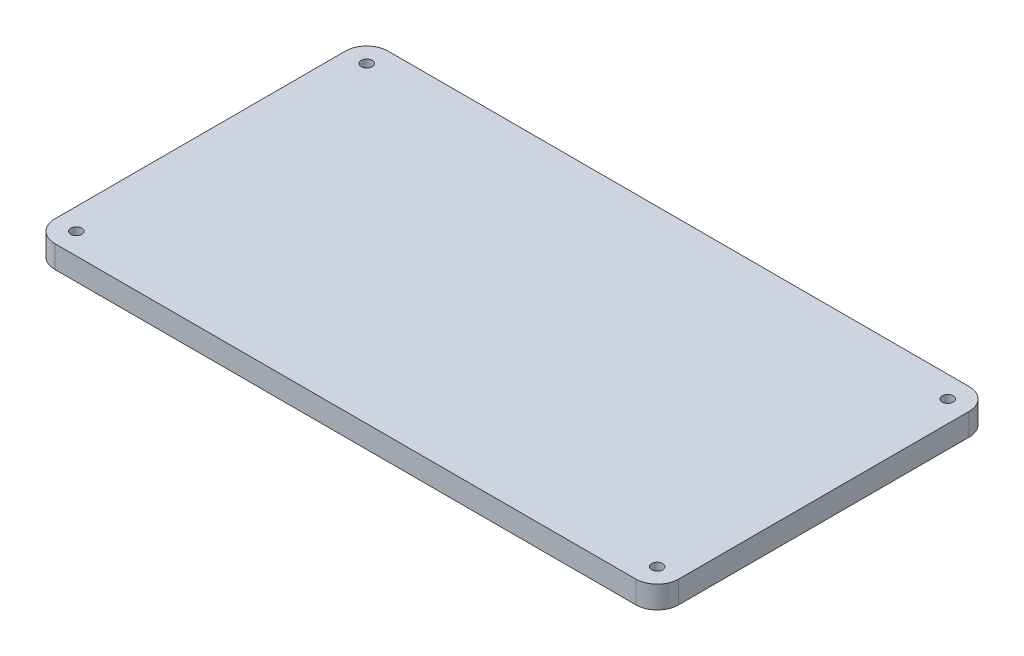
SolidWorks part; units mm, degrees
ref_plane "前视基准面" through (0, 0, 0) normal (0, 0, 1) x (1, 0, 0)
ref_plane "上视基准面" through (0, 0, 0) normal (0, 1, 0) x (1, 0, 0)
ref_plane "右视基准面" through (0, 0, 0) normal (1, 0, 0) x (0, 0, -1)
sketch "草图2" plane through (0, 0, 0) normal (0, 1, 0) x (1, 0, 0)
  line L0 (70, 27.5) -> (70, -37.5) construction
  line L1 (-65, -42.5) -> (65, -42.5) construction
  line L2 (-70, 27.5) -> (-70, -37.5) construction
  line L3 (-65, 32.5) -> (65, 32.5) construction
  line L4 (69.8, 27.5) -> (69.8, -37.5)
  line L5 (-65, -42.3) -> (65, -42.3)
  line L6 (-69.8, 27.5) -> (-69.8, -37.5)
  line L7 (-65, 32.3) -> (65, 32.3)
  arc A4 (-65, -42.5) -> (-70, -37.5) centre (-65, -37.5) cw construction
  arc A5 (65, -42.5) -> (70, -37.5) centre (65, -37.5) ccw construction
  arc A6 (-65, 32.5) -> (-70, 27.5) centre (-65, 27.5) ccw construction
  arc A7 (70, 27.5) -> (65, 32.5) centre (65, 27.5) ccw construction
  circle A8 centre (-65, 27.5) radius 1.225
  circle A9 centre (65, 27.5) radius 1.225
  circle A10 centre (65, -37.5) radius 1.225
  circle A11 centre (-65, -37.5) radius 1.225
  arc A12 (65, -42.3) -> (69.8, -37.5) centre (65, -37.5) ccw
  arc A13 (-65, -42.3) -> (-69.8, -37.5) centre (-65, -37.5) cw
  arc A14 (-65, 32.3) -> (-69.8, 27.5) centre (-65, 27.5) ccw
  arc A15 (69.8, 27.5) -> (65, 32.3) centre (65, 27.5) ccw
  dimension "D3" = 5
  dimension "D4" = 2.45
  dimension "D1" = 75
  dimension "D2" = 140
  dimension "D5" = 0.2
extrude "凸台-拉伸2" add sketch "草图2" along normal blind 5
